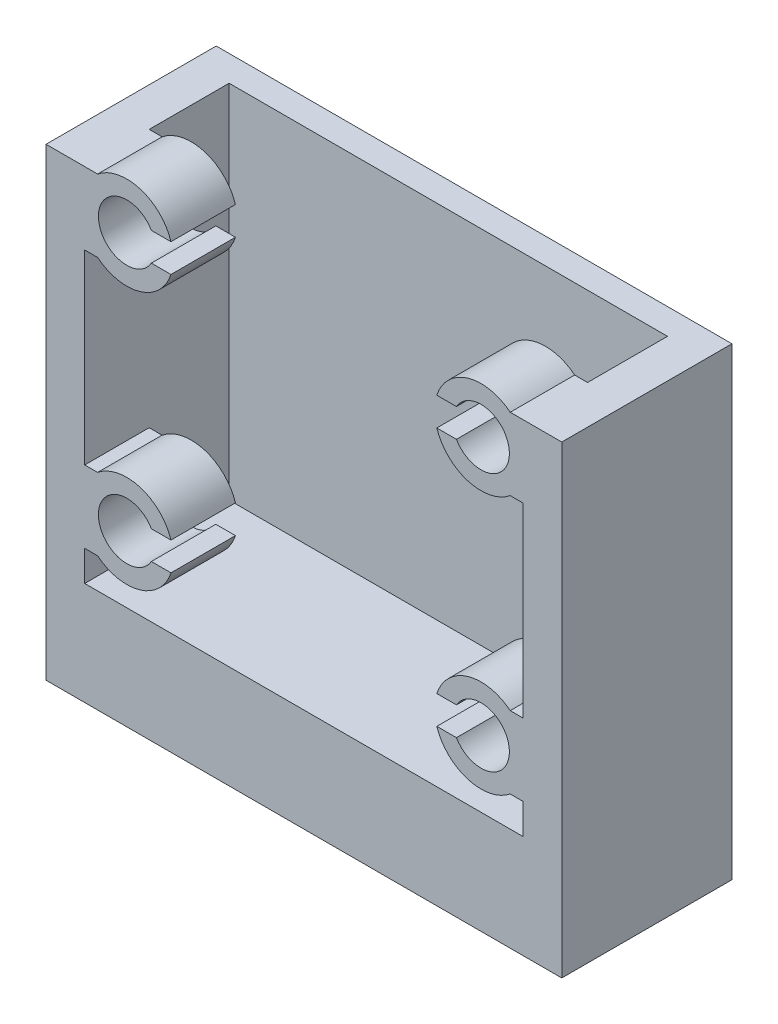
SolidWorks part; units mm, degrees
ref_plane "Plano frontal" through (0, 0, 0) normal (0, 0, 1) x (1, 0, 0)
ref_plane "Plano superior" through (0, 0, 0) normal (0, 1, 0) x (1, 0, 0)
ref_plane "Plano direito" through (0, 0, 0) normal (1, 0, 0) x (0, 0, -1)
sketch "Esboço1" plane through (0, 0, 0) normal (0, 0, 1) x (1, 0, 0)
  line L0 (0, 0) -> (-9, 0) construction
  line L2 (0, 2.75) -> (-4.7631, 2.75) construction
  line L3 (-4.7631, 2.75) -> (-8.5696, 2.75)
  line L4 (0, -2.75) -> (-4.7631, -2.75) construction
  line L5 (-4.7631, -2.75) -> (-8.5696, -2.75)
  line L6 (0, -2.75) -> (4.7631, -2.75) construction
  line L7 (4.7631, -2.75) -> (8.5696, -2.75) construction
  line L8 (0, 2.75) -> (4.7631, 2.75) construction
  line L9 (4.7631, 2.75) -> (8.5696, 2.75) construction
  line L10 (15.6569, -7) -> (15.6569, 7) construction
  line L11 (15.6569, 7) -> (5.6569, 7)
  line L12 (15.6569, -7) -> (5.6569, -7)
  line L13 (15.6569, 7) -> (15.6569, -7)
  line L14 (0, 0) -> (0, -50.1) construction
  line L15 (0, -25.05) -> (18.4015, -25.05) construction
  line L16 (15.6569, -43.1) -> (15.6569, -57.1) construction
  line L17 (4.7631, -52.85) -> (8.5696, -52.85) construction
  line L18 (0, -52.85) -> (4.7631, -52.85) construction
  line L19 (4.7631, -47.35) -> (8.5696, -47.35) construction
  line L20 (0, -47.35) -> (4.7631, -47.35) construction
  line L21 (0, -47.35) -> (-4.7631, -47.35) construction
  line L22 (0, -52.85) -> (-4.7631, -52.85) construction
  line L23 (0, -50.1) -> (-9, -50.1) construction
  line L24 (15.6569, -57.1) -> (15.6569, -43.1)
  line L25 (15.6569, -43.1) -> (5.6569, -43.1)
  line L26 (15.6569, -57.1) -> (5.6569, -57.1)
  line L27 (-4.7631, -47.35) -> (-8.5696, -47.35)
  line L28 (-4.7631, -52.85) -> (-8.5696, -52.85)
  arc A0 (-4.7631, -2.75) -> (-4.7631, 2.75) centre (0, 0) ccw
  arc A1 (-8.5696, -2.75) -> (5.6569, -7) centre (0, 0) ccw
  arc A2 (5.6569, -57.1) -> (-8.5696, -52.85) centre (0, -50.1) cw
  arc A3 (5.6569, 7) -> (-8.5696, 2.75) centre (0, 0) ccw
  arc A4 (-8.5696, -47.35) -> (5.6569, -43.1) centre (0, -50.1) cw
  arc A5 (-4.7631, -47.35) -> (-4.7631, -52.85) centre (0, -50.1) cw
  point P8 (0, 0)
  point P17 (15.6569, 0)
  point P37 (15.6569, -50.1)
  point P38 (0, -50.1)
  dimension "D1" = 11
  dimension "D2" = 18
  dimension "D3" = 5.5
  dimension "D4" = 14
  dimension "D5" = 10
  dimension "D6" = 50.1
  dimension "D7" = 5.5
  dimension "D8" = 3.8064
extrude "Ressalto-extrusão2" add sketch "Esboço1" along normal blind 12.5
ref_plane "Plano1" through (-34.3431, 0, 0) normal (1, 0, 0) x (0, 0, -1)
sketch "Esboço2" plane through (0, 0, 12.5) normal (0, 0, -1) x (-1, 0, 0)
  line L1 (-15.6569, 7) -> (-8.1569, 7)
  line L2 (-15.6569, 7) -> (-15.6569, -57.1)
  line L3 (-15.6569, -57.1) -> (-8.1569, -57.1)
  line L4 (-8.1569, 7) -> (-8.1569, -57.1)
  dimension "D1" = 7.5
extrude "Ressalto-extrusão3" add sketch "Esboço2" along normal blind 28
sketch "Esboço3" plane through (0, 0, -15.5) normal (0, 0, -1) x (-1, 0, 0)
  line L0 (34.3431, 6.875) -> (34.3431, -6.875) construction
  line L1 (-15.6569, 7) -> (34.3431, 7)
  line L2 (-15.6569, 7) -> (-15.6569, -83)
  line L3 (-15.6569, -83) -> (34.3431, -83)
  line L4 (34.3431, 7) -> (34.3431, -83)
  point P7 (0, 0)
  dimension "D1" = 90
extrude "Ressalto-extrusão4" add sketch "Esboço3" along normal blind 5
sketch "Esboço4" plane through (0, 0, -15.5) normal (0, 0, 1) x (1, 0, 0)
  line L0 (-34.3431, -6.875) -> (-34.3431, 6.875) construction
  line L1 (15.6569, -83) -> (-34.3431, -83)
  line L2 (15.6569, -83) -> (15.6569, -63)
  line L3 (8.1569, -63) -> (-34.3431, -63)
  line L4 (-34.3431, -83) -> (-34.3431, -63)
  line L5 (8.1569, -57.1) -> (8.1569, -63)
  line L6 (8.1569, -57.1) -> (15.6569, -57.1)
  line L7 (15.6569, -57.1) -> (15.6569, -63)
  dimension "D1" = 20
  dimension "D2" = 7.5
  dimension "D3" = 5.9
extrude "Ressalto-extrusão5" add sketch "Esboço4" along normal up to surface (28 mm away) up to face at (2.0607, -25.05, 12.5)
mirror "Espelhar4" about plane through (-34.3431, 0, 0) normal (1, 0, 0) of "Ressalto-extrusão5", "Ressalto-extrusão4", "Ressalto-extrusão3", "Ressalto-extrusão2"
mirror "Espelhar5" about plane through (-34.3431, 0, 0) normal (1, 0, 0) of "Ressalto-extrusão3"
mirror "Espelhar6" about plane through (-34.3431, 0, 0) normal (1, 0, 0) of "Ressalto-extrusão2"
